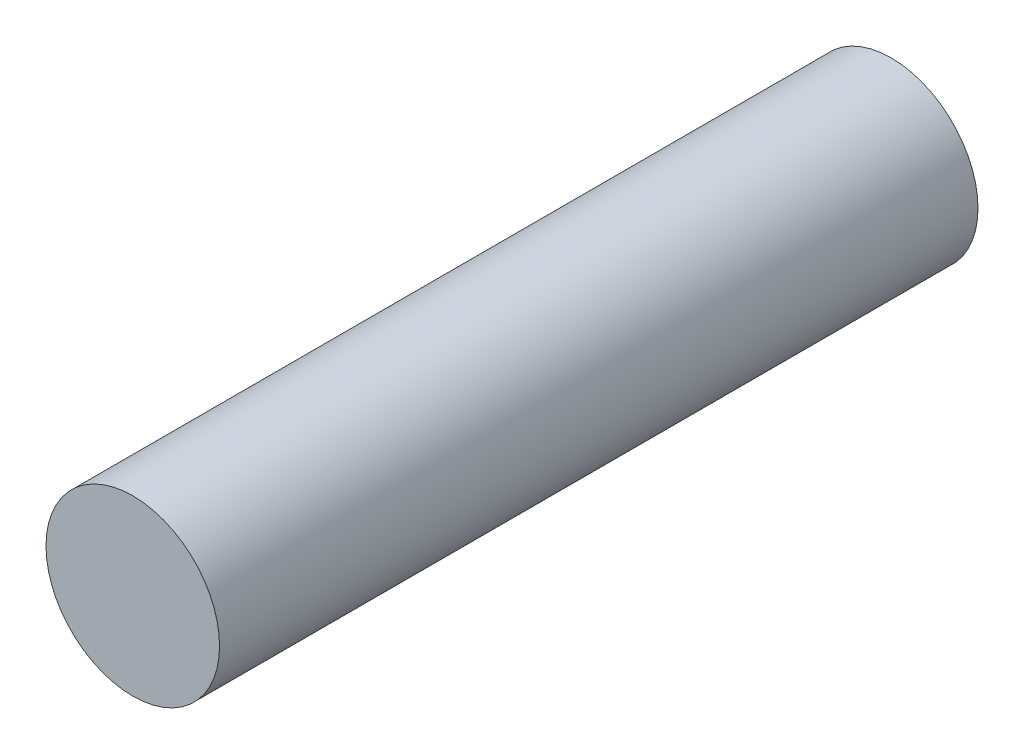
SolidWorks part; units mm, degrees
ref_plane "Plan de face" through (0, 0, 0) normal (0, 0, 1) x (1, 0, 0)
ref_plane "Plan de dessus" through (0, 0, 0) normal (0, 1, 0) x (1, 0, 0)
ref_plane "Plan de droite" through (0, 0, 0) normal (1, 0, 0) x (0, 0, -1)
sketch "Esquisse2" plane through (0, 0, 0) normal (0, 0, 1) x (1, 0, 0)
  circle A0 centre (0, 0) radius 49.403
  dimension "D1" = 98.806
extrude "Boss.-Extru.1" add sketch "Esquisse2" along normal blind 431.8
